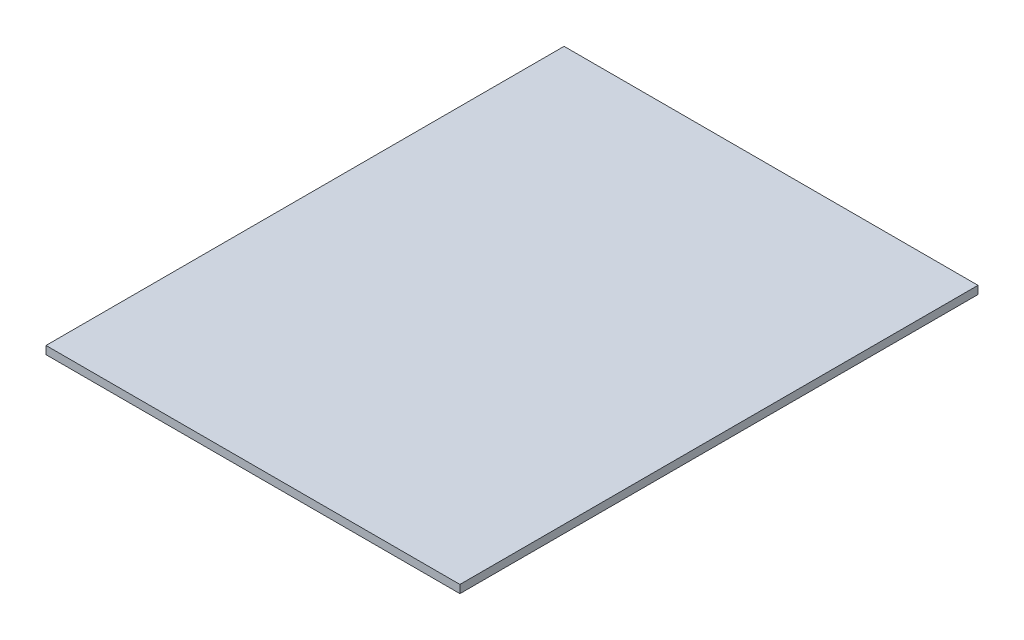
SolidWorks part; units mm, degrees
ref_plane "Alzado" through (0, 0, 0) normal (0, 0, 1) x (1, 0, 0)
ref_plane "Planta" through (0, 0, 0) normal (0, 1, 0) x (1, 0, 0)
ref_plane "Vista lateral" through (0, 0, 0) normal (1, 0, 0) x (0, 0, -1)
sketch "Croquis1" plane through (0, 0, 0) normal (0, 1, 0) x (1, 0, 0)
  line L1 (-118.4347, 112.3138) -> (191.5653, 112.3138)
  line L2 (-118.4347, 112.3138) -> (-118.4347, -275.6862)
  line L3 (-118.4347, -275.6862) -> (191.5653, -275.6862)
  line L4 (191.5653, 112.3138) -> (191.5653, -275.6862)
  dimension "D1" = 310
  dimension "D2" = 388
extrude "Saliente-Extruir1" add sketch "Croquis1" along normal blind 6
